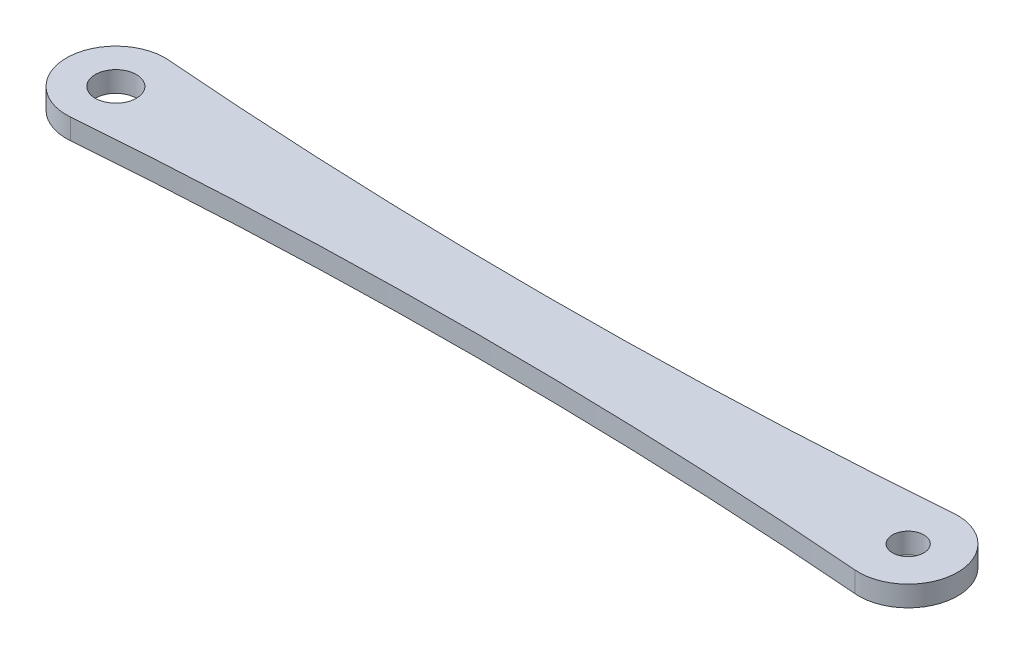
SolidWorks part; units mm, degrees
ref_plane "Front Plane" through (0, 0, 0) normal (0, 0, 1) x (1, 0, 0)
ref_plane "Top Plane" through (0, 0, 0) normal (0, 1, 0) x (1, 0, 0)
ref_plane "Right Plane" through (0, 0, 0) normal (1, 0, 0) x (0, 0, -1)
sketch "Sketch1" plane through (0, 0, 0) normal (0, 1, 0) x (1, 0, 0)
  line L0 (0, 0) -> (122.2878, 0) construction
  circle A0 centre (0, 0) radius 3.175
  circle A1 centre (0, 0) radius 7.62
  circle A2 centre (122.2878, 0) radius 2.413
  circle A3 centre (122.2878, 0) radius 7.62
  arc A4 (0.6054, 7.5959) -> (121.6824, 7.5959) centre (61.1439, 767.1873) ccw
  arc A5 (0.6054, -7.5959) -> (121.6824, -7.5959) centre (61.1439, -767.1873) cw
  point P10 (0, 0)
  point P11 (116.5898, -5.0593)
  dimension "D1" = 6.35
  dimension "D2" = 15.24
  dimension "D4" = 4.826
  dimension "D5" = 15.24
  dimension "D6" = 762
  dimension "D3" = 122.2878
extrude "Boss-Extrude1" add sketch "Sketch1" along normal blind 3.175
